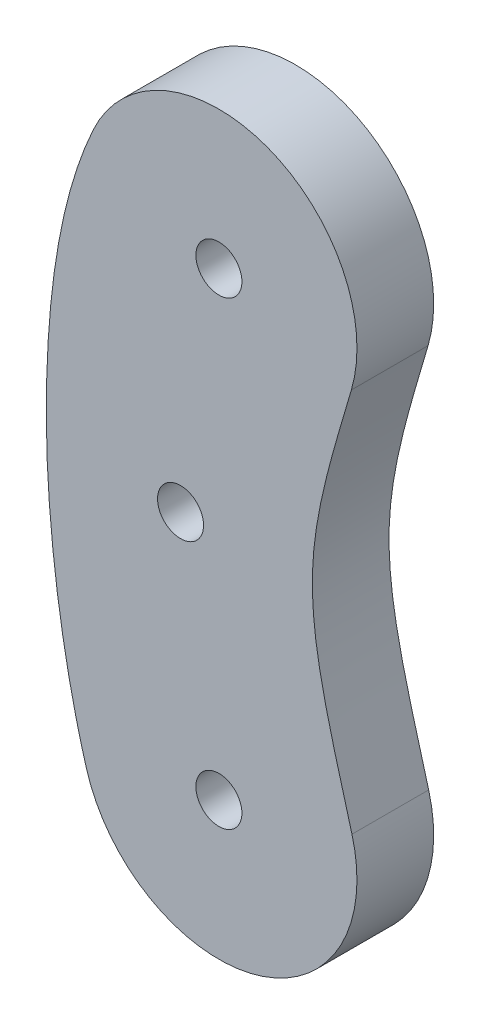
SolidWorks part; units mm, degrees
ref_plane "前视基准面" through (0, 0, 0) normal (0, 0, 1) x (1, 0, 0)
ref_plane "上视基准面" through (0, 0, 0) normal (0, 1, 0) x (1, 0, 0)
ref_plane "右视基准面" through (0, 0, 0) normal (1, 0, 0) x (0, 0, -1)
sketch "草图1" plane through (0, 0, 0) normal (0, 0, 1) x (1, 0, 0)
  line L0 (0, 0) -> (0, 30) construction
  circle A0 centre (0, 0) radius 9
  circle A1 centre (0, 30) radius 9
  spline S0 degree 3 poles (0, 30) (-4.9211, 20.7976) (-4.6963, 9.2577) (0, 0) knots 0 0 0 0 1 1 1 1 construction
  spline S1 degree 3 poles (-8.1776, 33.7586) (-10.2391, 29.2733) (-11.45, 20.9433) (-11.1137, 8.8833) (-9.7693, 1.2915) (-8.6293, -2.5565) knots 0 0 0 0 0.41277 0.646915 1 1 1 1
  spline S2 degree 3 poles (8.6737, 2.4014) (7.0759, 8.1724) (4.922, 15.3247) (7.4304, 23.3691) (8.634, 27.4595) knots 0 0 0 0 0.557288 1 1 1 1
  dimension "D2" = 18
  dimension "D3" = 18
  dimension "D1" = 30
extrude "凸台-拉伸1" add sketch "草图1" along normal blind 5
sketch "草图2" plane through (0, 0, 5) normal (0, 0, 1) x (1, 0, 0)
  circle A0 centre (0, 30) radius 1.5
  circle A1 centre (0, 0) radius 1.5
  dimension "D1" = 3
  dimension "D2" = 3
extrude "切除-拉伸1" cut sketch "草图2" against normal blind 10
sketch "草图3" plane through (0, 0, 5) normal (0, 0, 1) x (1, 0, 0)
  line L0 (0, 0) -> (0, 30) construction
  circle A0 centre (-2.5, 15) radius 1.5
  circle A1 centre (0, 30) radius 1.5 construction
  dimension "D1" = 15
  dimension "D2" = 2.5
  dimension "D3" = 3
extrude "切除-拉伸2" cut sketch "草图3" against normal blind 10
